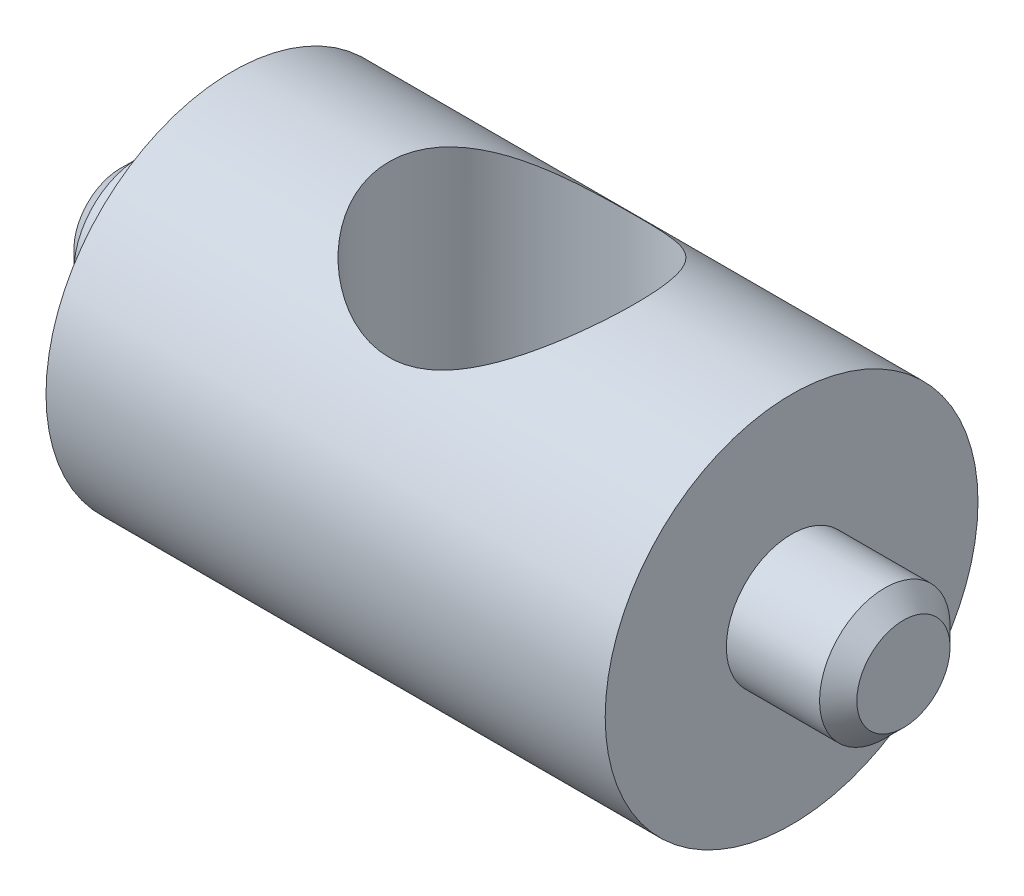
SolidWorks part; units mm, degrees
ref_plane "Piano frontale" through (0, 0, 0) normal (0, 0, 1) x (1, 0, 0)
ref_plane "Piano superiore" through (0, 0, 0) normal (0, 1, 0) x (1, 0, 0)
ref_plane "Piano destro" through (0, 0, 0) normal (1, 0, 0) x (0, 0, -1)
sketch "Schizzo1" plane through (0, 0, 0) normal (0, 0, 1) x (1, 0, 0)
  line L0 (-35.9326, 0) -> (21.3126, 0) construction
  line L1 (-21, 0) -> (-21, 1.75)
  line L2 (-21, 1.75) -> (-18, 1.75)
  line L3 (-18, 1.75) -> (-18, 5)
  line L4 (-18, 5) -> (-3, 5)
  line L5 (-3, 5) -> (-3, 1.75)
  line L6 (-3, 1.75) -> (0, 1.75)
  line L7 (0, 1.75) -> (0, 0)
  line L8 (0, 0) -> (-21, 0)
  point P5 (-8.0167, 5)
  point P12 (0, 0)
  point P13 (-35.9326, 0)
  dimension "D1" = 21
  dimension "D2" = 15
  dimension "D3" = 3.5
  dimension "D4" = 10
  dimension "D5" = 3
revolve "Rivoluzione1" add sketch "Schizzo1" angle 360 about L0
chamfer "Smusso1" distance 0.5 angle 45 2 edges at (0, 0, 1.75) (-21, 0, 1.75)
sketch "Schizzo2" plane through (0, 0, 0) normal (0, 1, 0) x (1, 0, 0)
  line L0 (-21, 0) -> (0, 0) construction
  line L1 (-21, 1.25) -> (-21, -1.25) construction
  line L2 (-10.5, -5) -> (-10.5, 5) construction
  line L3 (-18, -5) -> (-3, -5) construction
  line L4 (-3, 5) -> (-18, 5) construction
  circle A0 centre (-10.5, 0) radius 3
  dimension "D1" = 6
hole_wizard "Foro per Vite M6-2" positions "Schizzo3D2" profile "Schizzo3" hole size "M6" standard "Ansi Metric" end condition through all
sketch3d "Schizzo3D2"
  point P0 (-10.5, 5, 0)
  point P3 (0, 0, 0)
sketch "Schizzo3" plane through (-10.5, 5, 0) normal (1, 0, 0) x (0, 0, 1)
  line L0 (0, 0) -> (0, 10)
  line L1 (0, 10) -> (3.3, 10)
  line L2 (3.3, 10) -> (3.3, 0)
  line L5 (3.3, 0) -> (0, 0)
  line L11 (0, -6.35) -> (0, 107.95) construction
  dimension "Thru Hole Dia." = 6.6
  dimension "Thru Hole Depth" = 10
